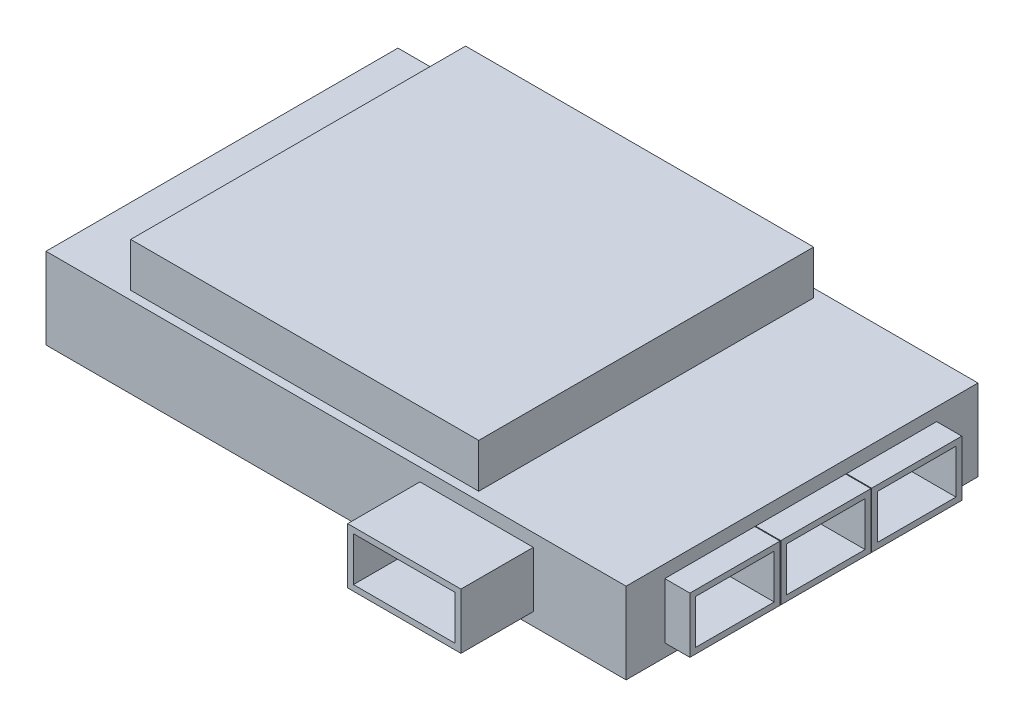
SolidWorks part; units mm, degrees
material "TM1000"
ref_plane "Front Plane" through (0, 0, 0) normal (0, 0, 1) x (1, 0, 0)
ref_plane "Top Plane" through (0, 0, 0) normal (0, 1, 0) x (1, 0, 0)
ref_plane "Right Plane" through (0, 0, 0) normal (1, 0, 0) x (0, 0, -1)
sketch "Sketch1" plane through (0, 0, 0) normal (0, 1, 0) x (1, 0, 0)
  line L1 (0, 0) -> (38.1, 0)
  line L2 (0, 0) -> (0, 23.114)
  line L3 (0, 23.114) -> (38.1, 23.114)
  line L4 (38.1, 0) -> (38.1, 23.114)
  dimension "D1" = 38.1
  dimension "D2" = 23.114
extrude "Boss-Extrude1" add sketch "Sketch1" along normal blind 5.334
sketch "Sketch2" plane through (0, 5.334, 0) normal (0, 1, 0) x (1, 0, 0)
  line L0 (0, 23.114) -> (0, 0) construction
  line L1 (5.0038, 22.5552) -> (27.8638, 22.5552)
  line L2 (5.0038, 22.5552) -> (5.0038, 0.5588)
  line L3 (5.0038, 0.5588) -> (27.8638, 0.5588)
  line L4 (27.8638, 22.5552) -> (27.8638, 0.5588)
  line L5 (10.2043, 23.114) -> (10.2043, 22.5552) construction
  line L6 (38.1, 23.114) -> (0, 23.114) construction
  line L7 (10.2043, 0.5588) -> (10.2043, 0) construction
  line L8 (0, 0) -> (38.1, 0) construction
  dimension "D1" = 22.86
  dimension "D2" = 21.9964
  dimension "D3" = 27.8638
extrude "Boss-Extrude2" add sketch "Sketch2" along normal blind 2.8956
sketch "Sketch3" plane through (0, 0, 0) normal (0, 0, 1) x (1, 0, 0)
  line L0 (27.3687, 0.8382) -> (27.3687, 0)
  line L1 (24.5618, 4.4958) -> (32.004, 4.4958)
  line L2 (24.5618, 4.4958) -> (24.5618, 0.8382)
  line L3 (24.5618, 0.8382) -> (32.004, 0.8382)
  line L4 (32.004, 4.4958) -> (32.004, 0.8382)
  line L5 (0, 0) -> (38.1, 0) construction
  line L6 (27.2439, 4.4958) -> (27.2439, 5.334)
  line L7 (5.0038, 5.334) -> (27.8638, 5.334) construction
  line L8 (38.1, 5.334) -> (38.1, 0) construction
  dimension "D1" = 7.4422
  dimension "D2" = 3.6576
  dimension "D3" = 13.5382
extrude "Boss-Extrude3" add sketch "Sketch3" along normal blind 4.7498 contours L4 L1 L2 L3
sketch "Sketch4" plane through (0, 0, 4.7498) normal (0, 0, 1) x (1, 0, 0)
  line L0 (24.5618, 4.4958) -> (32.004, 4.4958) construction
  line L1 (24.9428, 4.1148) -> (31.623, 4.1148)
  line L2 (24.9428, 4.1148) -> (24.9428, 1.2192)
  line L3 (24.9428, 1.2192) -> (31.623, 1.2192)
  line L4 (31.623, 4.1148) -> (31.623, 1.2192)
  line L5 (28.027, 4.4958) -> (28.027, 4.1148) construction
  line L6 (28.027, 1.2192) -> (28.027, 0.8382)
  line L7 (24.5618, 0.8382) -> (32.004, 0.8382) construction
  line L8 (24.5618, 2.5653) -> (24.9428, 2.5653)
  line L9 (24.5618, 4.4958) -> (24.5618, 0.8382) construction
  line L10 (31.623, 2.5653) -> (32.004, 2.5653)
  line L11 (32.004, 4.4958) -> (32.004, 0.8382) construction
  dimension "D1" = 0.381
extrude "Cut-Extrude1" cut sketch "Sketch4" against normal blind 3.556 contours L4 L1 L2 L3
sketch "Sketch5" plane through (38.1, 0, 0) normal (1, 0, 0) x (0, 0, -1)
  line L0 (-4.7498, 4.4958) -> (-4.7498, 0.8382) construction
  line L1 (2.54, 4.4958) -> (8.4582, 4.4958)
  line L2 (2.54, 4.4958) -> (2.54, 0.8382)
  line L3 (2.54, 0.8382) -> (8.4582, 0.8382)
  line L4 (8.4582, 4.4958) -> (8.4582, 0.8382)
  line L5 (0, 5.334) -> (0, 0) construction
  line L6 (2.9148, 5.334) -> (2.9148, 4.4958) construction
  line L7 (0, 5.334) -> (23.114, 5.334) construction
  line L8 (3.0273, 0.8382) -> (3.0273, 0) construction
  line L9 (0, 0) -> (23.114, 0) construction
  dimension "D1" = 5.9182
  dimension "D2" = 8.4582
extrude "Boss-Extrude4" add sketch "Sketch5" along normal blind 1.651
sketch "Sketch6" plane through (39.751, 0, 0) normal (1, 0, 0) x (0, 0, -1)
  line L0 (3.2654, 4.4958) -> (3.2654, 4.1148) construction
  line L1 (2.921, 4.1148) -> (8.0772, 4.1148)
  line L2 (2.921, 4.1148) -> (2.921, 1.2192)
  line L3 (2.921, 1.2192) -> (8.0772, 1.2192)
  line L4 (8.0772, 4.1148) -> (8.0772, 1.2192)
  line L5 (8.4582, 4.4958) -> (2.54, 4.4958) construction
  line L7 (3.2654, 1.2192) -> (3.2654, 0.8382) construction
  line L8 (2.54, 0.8382) -> (8.4582, 0.8382) construction
  line L9 (2.54, 3.2148) -> (2.921, 3.2148) construction
  line L10 (2.54, 4.4958) -> (2.54, 0.8382) construction
  line L12 (8.0772, 3.2148) -> (8.4582, 3.2148) construction
  line L13 (8.4582, 0.8382) -> (8.4582, 4.4958) construction
  dimension "D1" = 0.381
extrude "Cut-Extrude2" cut sketch "Sketch6" against normal blind 3.3782
pattern_linear "LPattern1" count 3 spacing 5.969 along (0, 0, -1) of "Boss-Extrude4", "Cut-Extrude2"
